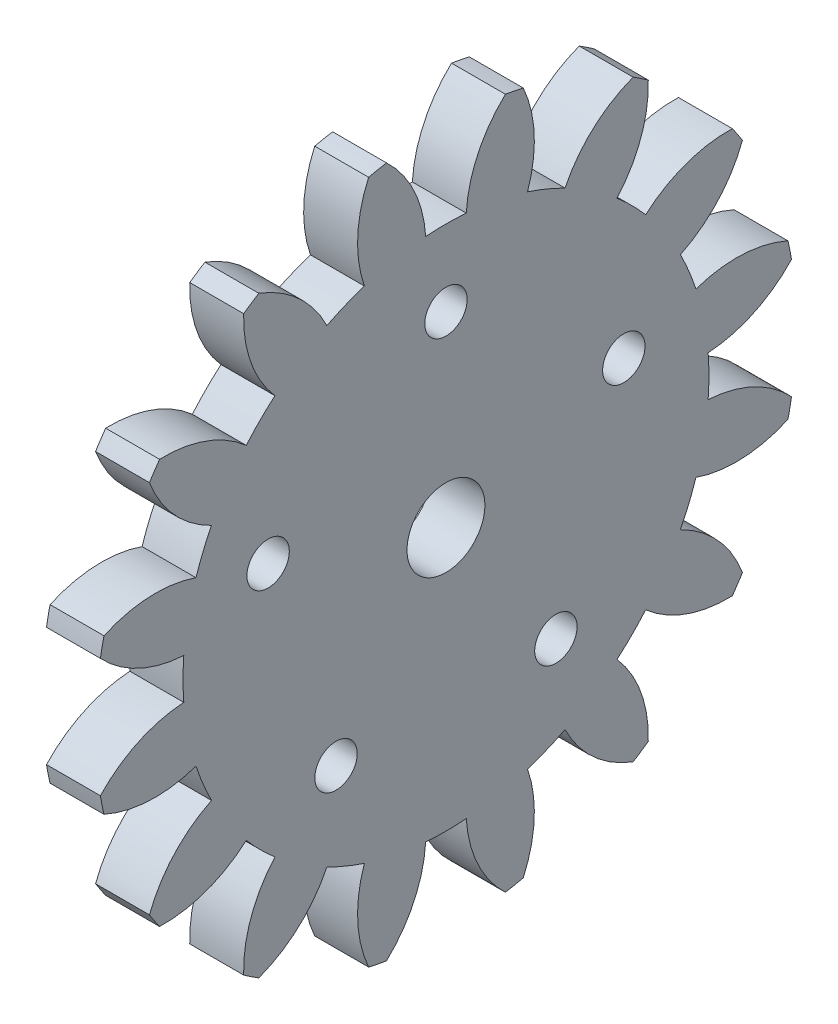
SolidWorks part; units mm, degrees
ref_plane "Plane1" through (0, 0, 0) normal (0, 0, 1) x (1, 0, 0)
ref_plane "Plane2" through (0, 0, 0) normal (0, 1, 0) x (1, 0, 0)
ref_plane "Plane3" through (0, 0, 0) normal (1, 0, 0) x (0, 0, -1)
sketch "HoldingSke" plane through (0, 0, 0) normal (0, 1, 0) x (1, 0, 0)
  line L0 (0, 0) -> (195.3284, -56.0095)
  line L1 (-15, 0) -> (100, 0) construction
  line L2 (0, 0) -> (-2.1039, 2.3779)
  line L3 (0, 0) -> (-11.863, 4.5341)
  line L4 (0, 0) -> (8.3015, 2.3804)
  line L5 (0, 0) -> (-47.5972, -17.7524)
  line L6 (0, 0) -> (-9.7909, -6.6059)
  line L7 (-2.1039, 2.3779) -> (8.8308, 51.9871)
  line L8 (-76.2, 54.61) -> (-75.184, 54.61)
  line L9 (-71.009, 38.7566) -> (-53.1078, 45.2721)
  line L10 (-76.2, 71.12) -> (104.1128, 71.12)
  line L11 (0, 0) -> (-11.811, 0)
  line L12 (-76.2, 101.6) -> (-76.0857, 101.6)
  line L13 (24.9733, 27.94) -> (52.9518, 28.4284)
  line L14 (24.9733, 27.94) -> (24.9746, 27.94)
  line L15 (24.9733, 27.94) -> (100.4006, 29.5858)
  circle A0 centre (0, 0) radius 0.3969
  circle A1 centre (0, 0) radius 21.43
  circle A2 centre (0, 0) radius 38.1
  circle A3 centre (0, 0) radius 0.3969
  dimension "MHD" = 42.86
  dimension "Hub_dia" = 76.2
  dimension "Bore" = 0.7937
  dimension "MBD" = 0.7937
  dimension "Num_teeth" = 16
  dimension "Pitch_radius" = 180.3128
  dimension "Pitch" = 203.2
  dimension "Width" = 11.811
  dimension "Overall_len" = 50.8
  dimension "Show_teeth" = 16
  dimension "Thickness" = 11.811
  dimension "OAL" = 50.8001
  dimension "T_dim" = 1.016
  dimension "Ap" = 20
  dimension "H" = 19.05
  dimension "Backlash" = 0.1143
  dimension "Addendum_fac" = 1
  dimension "Dedendum_fac" = 1.25
  dimension "Clearance_fac" = 0.25
  dimension "Dedendum_add" = 0.0013
sketch "BasProSke" plane through (0, 0, 0) normal (0, 1, 0) x (1, 0, 0)
  line L0 (-10, 0) -> (60, 0) construction
  line L1 (0, 0) -> (0, 28.575)
  line L2 (0, 0) -> (11.811, 0)
  line L3 (11.811, 0) -> (11.811, 28.575)
  line L4 (11.811, 28.575) -> (0, 28.575)
  dimension "Diameter" = 57.15
  dimension "Thickness" = 11.811
revolve "Base-Revolve" add sketch "BasProSke" angle 360 about L0
sketch "TooCutSke" plane through (0, 0, 0) normal (1, 0, 0) x (0, 0, -1)
  line L1 (0, 0) -> (0, 107) construction
  line L2 (0, 0) -> (-2.6895, 25.2572) construction
  line L3 (0, 0) -> (-9.8702, 49.6211) construction
  line L4 (-2.6895, 25.2572) -> (-4.9351, 24.8105) construction
  arc A0 (1.6538, 21.3661) -> (-1.6538, 21.3661) centre (0, 0) ccw
  arc A1 (4.8685, 28.183) -> (-4.8685, 28.183) centre (0, 0) ccw
  circle A2 centre (0, 0) radius 25.4 construction
  circle A3 centre (0, 0) radius 23.8682 construction
  arc A4 (-1.6538, 21.3661) -> (-4.8685, 28.183) centre (-11.7951, 20.7501) ccw
  arc A5 (4.8685, 28.183) -> (1.6538, 21.3661) centre (11.7951, 20.7501) ccw
  dimension "Root_dia" = 42.86
  dimension "Overcut_dia" = 57.2008
  dimension "Pitch_dia" = 50.8
  dimension "Base_dia" = 47.7364
  dimension "Flank_rad" = 10.16
  dimension "Half_ang" = 11.25
  dimension "Half_CT" = 2.2896
extrude "ToothCut" cut sketch "TooCutSke" along normal through all
fillet "Breaks" [suppressed] radius 0.0635
fillet "RootFillets" [suppressed] radius 0.795
pattern_circular "TeethCuts" count 16 every 22.5 about axis through (-10, 0, 0) along (1, 0, 0) of "ToothCut", "RootFillets", "Breaks"
sketch "HubNeaOneSke" plane through (0, 0, 0) normal (-1, 0, 0) x (0, 0, 1)
  circle A0 centre (0, 0) radius 21.43
  dimension "Diameter" = 42.86
extrude "HubNearOne" [suppressed] add sketch "HubNeaOneSke" along normal blind 38.9891
sketch "HubNeaBotSke" plane through (0, 0, 0) normal (-1, 0, 0) x (0, 0, 1)
  circle A0 centre (0, 0) radius 21.43
  dimension "Diameter" = 42.86
extrude "HubNearBoth" [suppressed] add sketch "HubNeaBotSke" along normal blind 19.4945
ref_plane "FarPln" through (11.811, 0, 0) normal (1, 0, 0) x (0, 0, -1)
sketch "HubFarSke" plane through (11.811, 0, 0) normal (1, 0, 0) x (0, 0, -1)
  circle A0 centre (0, 0) radius 21.43
  dimension "Diameter" = 42.86
extrude "HubFar" [suppressed] add sketch "HubFarSke" along normal blind 19.4945
sketch "BorSke" plane through (0, 0, 0) normal (1, 0, 0) x (0, 0, -1)
  circle A0 centre (0, 0) radius 0.3969
  dimension "Diameter" = 0.7937
extrude "Bore" cut sketch "BorSke" along normal mid plane 101.6001
sketch "KeySke" plane through (0, 0, 0) normal (1, 0, 0) x (0, 0, -1)
  line L0 (-0.127, 0) -> (-0.127, 0.6191)
  line L1 (-0.127, 0.6191) -> (0.127, 0.6191)
  line L2 (0.127, 0.6191) -> (0.127, 0)
  line L3 (0, 0) -> (0, 34) construction
  line L4 (-0.127, 0) -> (0.127, 0)
  dimension "Offset" = 0.6191
  dimension "Width" = 0.254
extrude "Keyway" [suppressed] cut sketch "KeySke" along normal mid plane 101.6001
pattern_circular "Keyway2" [suppressed] count 2 every 90 about axis through (-10, 0, 0) along (1, 0, 0)
sketch "Sketch1" plane through (11.811, 0, 0) normal (1, 0, 0) x (0, 0, -1)
  circle A0 centre (0, 0) radius 3.175
  dimension "D1" = 6.35
extrude "Cut-Extrude1" cut sketch "Sketch1" against normal through all
sketch "Sketch2" plane through (11.811, 0, 0) normal (1, 0, 0) x (0, 0, -1)
  line L0 (0, 0) -> (0, 25.415) construction
  circle A0 centre (0, 15.24) radius 1.7272
  circle A1 centre (14.4941, 4.7094) radius 1.7272
  circle A2 centre (8.9578, -12.3294) radius 1.7272
  circle A3 centre (-8.9578, -12.3294) radius 1.7272
  circle A4 centre (-14.4941, 4.7094) radius 1.7272
  point P15 (0, 0)
  dimension "D1" = 3.4544
  dimension "D2" = 15.24
  dimension "D3" = 5
extrude "Cut-Extrude2" cut sketch "Sketch2" against normal through all
sketch "Sketch3" plane through (0, 0, 0) normal (-1, 0, 0) x (0, 0, 1)
  line L1 (-40.957, 29.2227) -> (43.5206, 29.2227)
  line L2 (-40.957, 29.2227) -> (-40.957, -31.399)
  line L3 (-40.957, -31.399) -> (43.5206, -31.399)
  line L4 (43.5206, 29.2227) -> (43.5206, -31.399)
extrude "Cut-Extrude3" cut sketch "Sketch3" against normal blind 7.4168
equation "' \"Pitch@HoldingSke\" = 4"
equation "' \"Num_teeth@HoldingSke\" = 12"
equation "' \"Ap@HoldingSke\" =  20"
equation "' \"Width@HoldingSke\" = 0.5"
equation "' \"Hub_dia@HoldingSke\"= 1"
equation "' \"Overall_len@HoldingSke\" = 1.0"
equation "' \"Bore@HoldingSke\" = 0.75"
equation "' \"T_dim@HoldingSke\" = 0.85"
equation "' \"Width@KeySke\" = 0.25"
equation "' \"Show_teeth@HoldingSke\" = 13"
equation "' \"Backlash@HoldingSke\" = 0.009"
equation "' \"Addendum_fac@HoldingSke\" = 1.0"
equation "' \"Dedendum_fac@HoldingSke\" = 1.25"
equation "' \"Dedendum_add@HoldingSke\" = 0.00005"
equation "' \"Clearance_fac@HoldingSke\" = 0.25"
equation "' \"Pitch@HoldingSke\" = 0.5"
equation "' \"Num_teeth@HoldingSke\" = 23"
equation "' \"Show_teeth@HoldingSke\" = 23"
equation "' \"Backlash@HoldingSke\" = 0.0375"
equation "\"Overcut_dia@TooCutSke\" = (\"Num_teeth@HoldingSke\" + 2 * \"Addendum_fac@HoldingSke\") / \"Pitch@HoldingSke\" + 0.002"
equation "\"Pitch_dia@TooCutSke\" = \"Num_teeth@HoldingSke\" / \"Pitch@HoldingSke\""
equation "\"Base_dia@TooCutSke\" = \"Num_teeth@HoldingSke\" / \"Pitch@HoldingSke\" * cos((\"Ap@HoldingSke\"  * 3.14159265 / 180))"
equation "\"Root_dia@TooCutSke\" = (\"Num_teeth@HoldingSke\" + 2) / \"Pitch@HoldingSke\" - 2 * (\"Addendum_fac@HoldingSke\" + \"Dedendum_fac@HoldingSke\") / \"Pitch@HoldingSke\" - \"Dedendum_add@HoldingSke\" * 2"
equation "\"Half_ang@TooCutSke\" = 180 / \"Num_teeth@HoldingSke\""
equation "\"Half_CT@TooCutSke\" = \"Num_teeth@HoldingSke\" / \"Pitch@HoldingSke\" * sin((3.14159265 / 2 / \"Num_teeth@HoldingSke\")) / 2 - 7 * \"Backlash@HoldingSke\" / 4"
equation "\"Flank_rad@TooCutSke\" = \"Num_teeth@HoldingSke\" / \"Pitch@HoldingSke\" / 5"
equation "\"Radius@RootFillets\" = \"Clearance_fac@HoldingSke\" / \"Pitch@HoldingSke\" + \"Dedendum_add@HoldingSke\""
equation "\"Break_rad@Breaks\" = 0.02 / \"Pitch@HoldingSke\""
equation "\"Thickness@HoldingSke\" = \"Width@HoldingSke\""
equation "\"OAL@HoldingSke\" = \"Thickness@HoldingSke\""
equation "\"MHD@HoldingSke\" = (\"Num_teeth@HoldingSke\" + 2) / \"Pitch@HoldingSke\" - 2 * (\"Addendum_fac@HoldingSke\" + \"Dedendum_fac@HoldingSke\")  / \"Pitch@HoldingSke\" - \"Dedendum_add@HoldingSke\" * 2"
equation "\"MBD@HoldingSke\" = (\"Num_teeth@HoldingSke\" + 2) / \"Pitch@HoldingSke\" - 2 * (\"Addendum_fac@HoldingSke\" + \"Dedendum_fac@HoldingSke\")  / \"Pitch@HoldingSke\" - \"Dedendum_add@HoldingSke\" * 2 - 0.002"
equation "\"MHD@HoldingSke\" = ((sgn( \"MHD@HoldingSke\" - \"Hub_dia@HoldingSke\" )-1)*( \"MHD@HoldingSke\" - \"Hub_dia@HoldingSke\" ))/-2+ \"Hub_dia@HoldingSke\""
equation "\"MBD@HoldingSke\" = ((sgn( \"MBD@HoldingSke\" - \"Bore@HoldingSke\" )-1)*( \"MBD@HoldingSke\" - \"Bore@HoldingSke\" ))/-2+ \"Bore@HoldingSke\""
equation "\"OAL@HoldingSke\" = ((sgn( \"OAL@HoldingSke\" - \"Overall_len@HoldingSke\" )+1)*( \"OAL@HoldingSke\" - \"Overall_len@HoldingSke\" ))/2 + \"Overall_len@HoldingSke\" + 0.000002"
equation "\"Num_teeth@TeethCuts\" = int( \"Show_teeth@HoldingSke\" ) + 1"
equation "\"Num_teeth@TeethCuts\" = ((sgn( \"Num_teeth@TeethCuts\" - \"Num_teeth@HoldingSke\" )-1)*( \"Num_teeth@TeethCuts\" - \"Num_teeth@HoldingSke\" ))/-2+ \"Num_teeth@HoldingSke\""
equation "\"Num_teeth@TeethCuts\" = ((sgn( \"Num_teeth@TeethCuts\" - 2.0)+1)*( \"Num_teeth@TeethCuts\" - 2.0))/2 +2.0"
equation "\"Angle@TeethCuts\" = 360.0 / \"Num_teeth@HoldingSke\""
equation "\"Diameter@BasProSke\" = (\"Num_teeth@HoldingSke\" + 2 * \"Addendum_fac@HoldingSke\") / \"Pitch@HoldingSke\""
equation "\"Thickness@BasProSke\"  = \"Thickness@HoldingSke\""
equation "' \"Fillet_rad@BasProSke\" =  \"Thickness@HoldingSke\" * 0.05"
equation "\"MHD@HoldingSke\" = ((sgn( \"MHD@HoldingSke\" - \"Root_dia@TooCutSke\" )-1)*( \"MHD@HoldingSke\" - \"Root_dia@TooCutSke\" ))/-2+ \"Root_dia@TooCutSke\""
equation "\"Diameter@HubNeaOneSke\" = \"MHD@HoldingSke\""
equation "\"Length@HubNearOne\" = \"OAL@HoldingSke\" - \"Thickness@BasProSke\""
equation "\"Diameter@HubNeaBotSke\" = \"MHD@HoldingSke\""
equation "\"Length@HubNearBoth\" = ( \"OAL@HoldingSke\" - \"Thickness@BasProSke\" ) / 2.0"
equation "\"Thickness@FarPln\" = \"Thickness@BasProSke\""
equation "\"Diameter@HubFarSke\" = \"MHD@HoldingSke\""
equation "\"Length@HubFar\" = ( \"OAL@HoldingSke\" - \"Thickness@BasProSke\" ) / 2.0"
equation "\"Diameter@BorSke\" = \"MBD@HoldingSke\""
equation "\"D1@Bore\" = \"OAL@HoldingSke\" * 2.0"
equation "\"D1@Keyway\" = \"OAL@HoldingSke\" * 2.0"
equation "\"Offset@KeySke\" = \"T_dim@HoldingSke\" - \"MBD@HoldingSke\" / 2.0"
